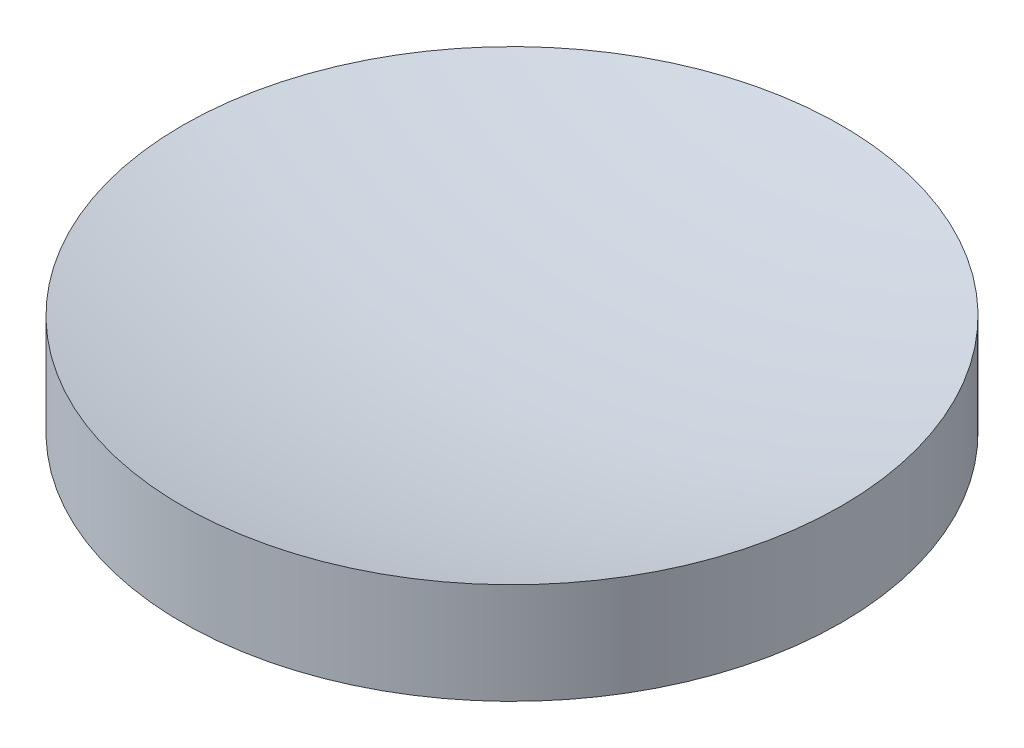
SolidWorks part; units mm, degrees
ref_plane "Plan de face" through (0, 0, 0) normal (0, 0, 1) x (1, 0, 0)
ref_plane "Plan de dessus" through (0, 0, 0) normal (0, 1, 0) x (1, 0, 0)
ref_plane "Plan de droite" through (0, 0, 0) normal (1, 0, 0) x (0, 0, -1)
sketch "Esquisse1" plane through (0, 0, 0) normal (0, 0, 1) x (1, 0, 0)
  line L0 (0, 0) -> (0, 160) construction
  line L2 (-20, -3.5908) -> (-20, 2.5403)
  line L3 (0, -5.9501) -> (0, 0)
  arc A0 (-20, 2.5403) -> (0, 0) centre (0, 80) ccw
  arc A1 (0, -5.9501) -> (-20, -3.5908) centre (0, 80) cw
  dimension "D1" = 80
  dimension "D2" = 20
revolve "Révolution3" add sketch "Esquisse1" angle 360 about L0
